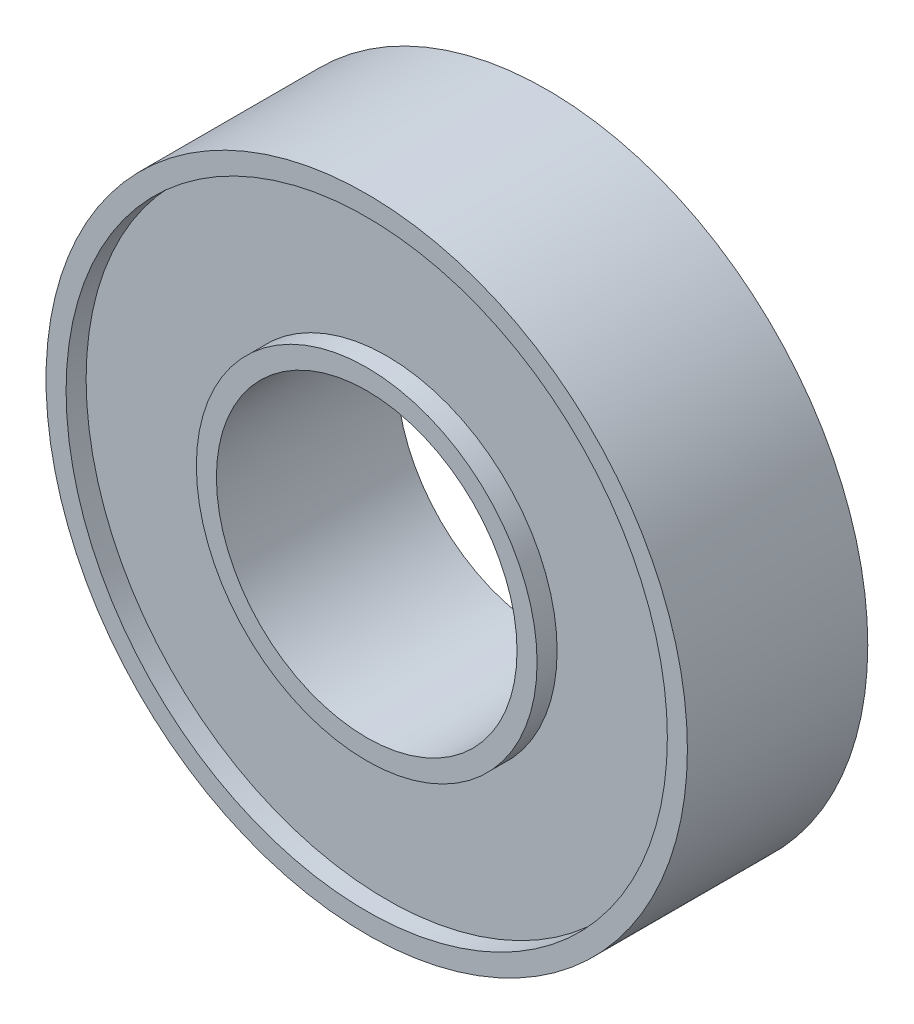
SolidWorks part; units mm, degrees
ref_plane "Front Plane" through (0, 0, 0) normal (0, 0, 1) x (1, 0, 0)
ref_plane "Top Plane" through (0, 0, 0) normal (0, 1, 0) x (1, 0, 0)
ref_plane "Right Plane" through (0, 0, 0) normal (1, 0, 0) x (0, 0, -1)
sketch "Sketch4" plane through (0, 0, 0) normal (1, 0, 0) x (0, 0, -1)
  line L0 (-4.5, 16) -> (4.5, 16)
  line L1 (4.5, 16) -> (4.5, 15)
  line L2 (4.5, 15) -> (3.5, 15)
  line L3 (3.5, 15) -> (3.5, 8.5)
  line L4 (3.5, 8.5) -> (4.5, 8.5)
  line L5 (4.5, 8.5) -> (4.5, 7.5)
  line L6 (4.5, 7.5) -> (-4.5, 7.5)
  line L7 (-12.5289, 0) -> (20.3939, 0) construction
  line L8 (-4.5, 8.5) -> (-4.5, 7.5)
  line L9 (-3.5, 8.5) -> (-4.5, 8.5)
  line L10 (-3.5, 15) -> (-3.5, 8.5)
  line L11 (-4.5, 15) -> (-3.5, 15)
  line L12 (-4.5, 16) -> (-4.5, 15)
  point P12 (0, 7.5)
  point P13 (0, 16)
  dimension "D1" = 4.5
  dimension "D2" = 1
  dimension "D3" = 1
  dimension "D4" = 16
  dimension "D6" = 1
revolve "Revolve3" add sketch "Sketch4" angle 360 about L7
